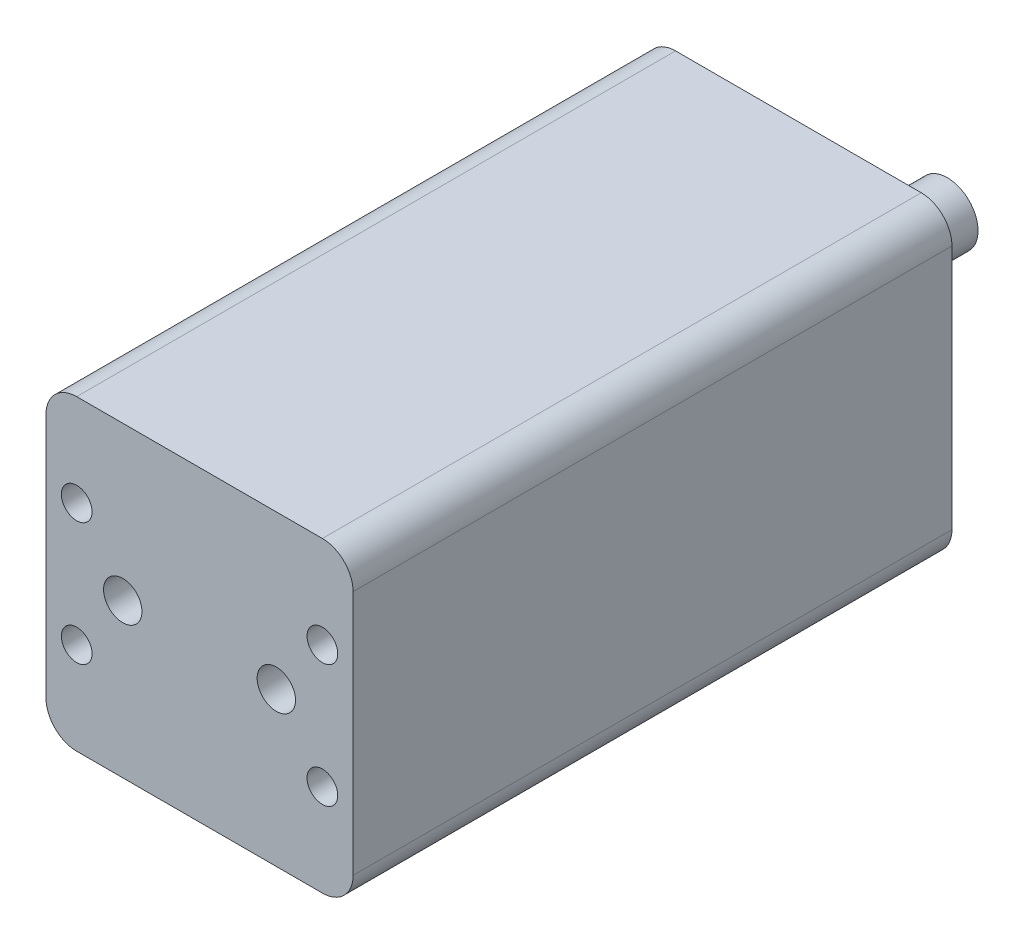
SolidWorks part; units mm, degrees
ref_plane "Front Plane" through (0, 0, 0) normal (0, 0, 1) x (1, 0, 0)
ref_plane "Top Plane" through (0, 0, 0) normal (0, 1, 0) x (1, 0, 0)
ref_plane "Right Plane" through (0, 0, 0) normal (1, 0, 0) x (0, 0, -1)
sketch "Sketch3" plane through (0, 0, 0) normal (0, 0, 1) x (1, 0, 0)
  line L1 (-16, -20) -> (16, -20)
  line L2 (-20, -16) -> (-20, 16)
  line L3 (-16, 20) -> (16, 20)
  line L4 (20, -16) -> (20, 16)
  line L5 (-20, -20) -> (20, 20) construction
  line L6 (-20, 20) -> (20, -20) construction
  arc A0 (-16, -20) -> (-20, -16) centre (-16, -16) cw
  arc A1 (16, -20) -> (20, -16) centre (16, -16) ccw
  arc A2 (16, 20) -> (20, 16) centre (16, 16) cw
  arc A3 (-20, 16) -> (-16, 20) centre (-16, 16) cw
  point P0 (0, 0)
  dimension "D2" = 4
  dimension "D1" = 40
extrude "Boss-Extrude1" add sketch "Sketch3" along normal blind 78
sketch "Sketch4" plane through (0, 0, 0) normal (0, 0, -1) x (-1, 0, 0)
  circle A0 centre (0, 0) radius 16
  dimension "D1" = 32
extrude "Boss-Extrude2" add sketch "Sketch4" along normal blind 3
sketch "Sketch5" plane through (0, 0, -3) normal (0, 0, -1) x (-1, 0, 0)
  circle A0 centre (0, 0) radius 4
  dimension "D1" = 8
extrude "Boss-Extrude3" add sketch "Sketch5" along normal blind 16.4
sketch "Sketch7" plane through (0, 0, 0) normal (0, 0, -1) x (-1, 0, 0)
  line L0 (0, 0) -> (-15.5, 15.5) construction
  line L1 (-15.5, 15.5) -> (15.5, 15.5) construction
  line L2 (15.5, 15.5) -> (0, 0) construction
  circle A1 centre (-15.5, 15.5) radius 2
  circle A3 centre (15.5, 15.5) radius 2
  circle A4 centre (15.5, -15.5) radius 2
  circle A5 centre (-15.5, -15.5) radius 2
  dimension "D1" = 4
  dimension "D2" = 4
extrude "Cut-Extrude2" cut sketch "Sketch7" against normal blind 9
sketch "Sketch8" plane through (0, 0, 78) normal (0, 0, 1) x (1, 0, 0)
  line L0 (0, 0) -> (-16, 0) construction
  line L1 (-16, 0) -> (-16, 8) construction
  line L2 (-16, 8) -> (0, 0) construction
  line L3 (0, 0) -> (0, 8) construction
  line L4 (0, 8) -> (-16, 8) construction
  line L5 (0, 0) -> (16, 8) construction
  line L6 (16, 8) -> (16, -8) construction
  line L7 (16, -8) -> (0, 0) construction
  line L8 (0, 0) -> (16, 0) construction
  circle A0 centre (-16, 8) radius 2
  circle A1 centre (16, 8) radius 2
  circle A2 centre (-16, -8) radius 2
  circle A3 centre (16, -8) radius 2
  dimension "D3" = 4
  dimension "D1" = 16
  dimension "D2" = 8
extrude "Cut-Extrude3" cut sketch "Sketch8" against normal blind 10
sketch "Sketch9" plane through (0, 0, 78) normal (0, 0, 1) x (1, 0, 0)
  line L0 (0, 0) -> (10, 0) construction
  line L1 (0, 0) -> (0, 7.9506) construction
  circle A0 centre (10, 0) radius 2.5
  circle A1 centre (-10, 0) radius 2.5
  dimension "D1" = 5
extrude "Cut-Extrude4" cut sketch "Sketch9" against normal blind 10
